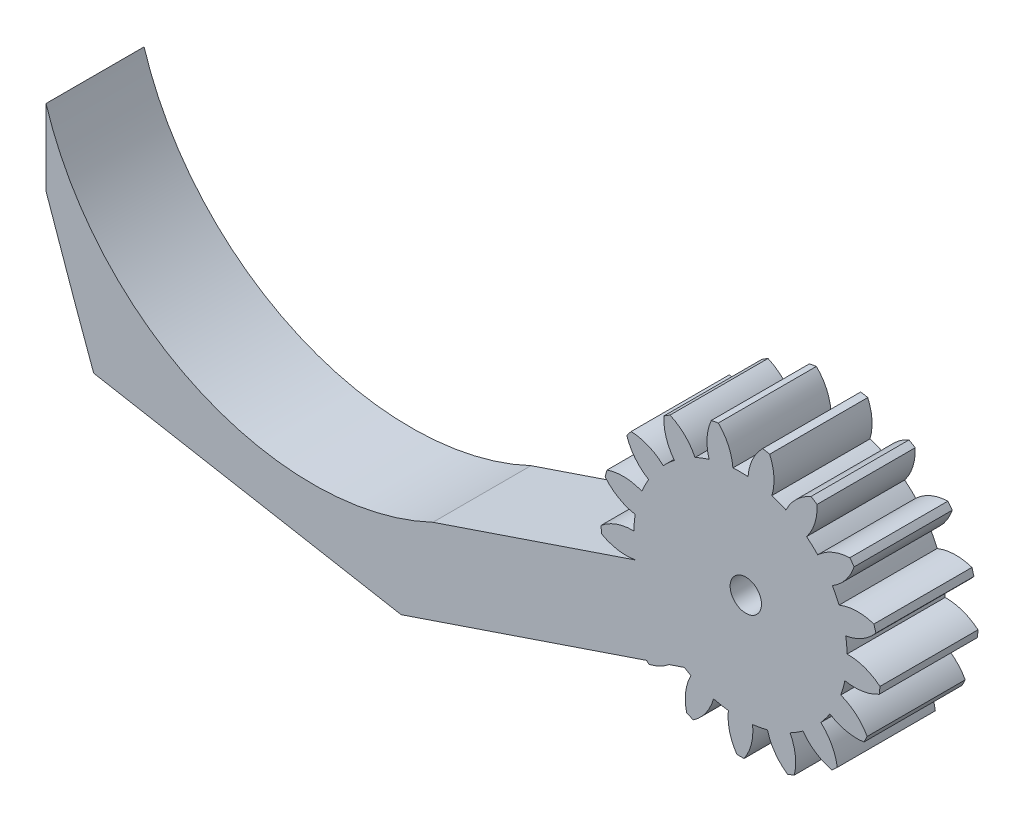
SolidWorks part; units mm, degrees
ref_plane "前视基准面" through (0, 0, 0) normal (0, 0, 1) x (1, 0, 0)
ref_plane "上视基准面" through (0, 0, 0) normal (0, 1, 0) x (1, 0, 0)
ref_plane "右视基准面" through (0, 0, 0) normal (1, 0, 0) x (0, 0, -1)
other "Configuration Table"
sketch "草图1" plane through (0, 0, 0) normal (0, 0, 1) x (1, 0, 0)
  circle A0 centre (-0.5445, -0.2729) radius 12.75 construction
  arc A1 (-14.346, 3.2738) -> (-11.274, 1.4939) centre (-10.4132, 6.5208) ccw
  arc A2 (-11.274, 1.4939) -> (-11.4159, -0.0382) centre (-0.5445, -0.2729) ccw
  arc A3 (-11.4159, -0.0382) -> (-14.7627, -1.2233) centre (-11.4935, -5.1376) ccw
  arc A4 (-14.7627, -1.2233) -> (-14.6953, -1.9514) centre (-0.5445, -0.2729) ccw
  arc A5 (-14.6953, -1.9514) -> (-11.1877, -2.5013) centre (-12.2009, 2.497) ccw
  arc A6 (-11.1877, -2.5013) -> (-10.7666, -3.9813) centre (-0.5445, -0.2729) ccw
  arc A7 (-10.7666, -3.9813) -> (-13.4593, -6.2953) centre (-8.9968, -8.7644) ccw
  arc A8 (-13.4593, -6.2953) -> (-13.1334, -6.9499) centre (-0.5445, -0.2729) ccw
  arc A9 (-13.1334, -6.9499) -> (-9.664, -6.1956) centre (-12.4144, -1.9008) ccw
  arc A10 (-9.664, -6.1956) -> (-8.7367, -7.4235) centre (-0.5445, -0.2729) ccw
  arc A11 (-8.7367, -7.4235) -> (-10.4117, -10.554) centre (-5.3586, -11.2443) ccw
  arc A12 (-10.4117, -10.554) -> (-9.8713, -11.0467) centre (-0.5445, -0.2729) ccw
  arc A13 (-9.8713, -11.0467) -> (-6.9087, -9.09) centre (-11.0248, -6.0788) ccw
  arc A14 (-6.9087, -9.09) -> (-5.6004, -9.9) centre (-0.5445, -0.2729) ccw
  arc A15 (-5.6004, -9.9) -> (-6.0314, -13.4242) centre (-1.0702, -12.2425) ccw
  arc A16 (-6.0314, -13.4242) -> (-5.3495, -13.6884) centre (-0.5445, -0.2729) ccw
  arc A17 (-5.3495, -13.6884) -> (-3.2938, -10.7936) centre (-8.2198, -9.4727) ccw
  arc A18 (-3.2938, -10.7936) -> (-1.7813, -11.0764) centre (-0.5445, -0.2729) ccw
  arc A19 (-1.7813, -11.0764) -> (-0.9101, -14.5183) centre (3.2892, -11.6241) ccw
  arc A20 (-0.9101, -14.5183) -> (-0.1788, -14.5183) centre (-0.5445, -0.2729) ccw
  arc A21 (-0.1788, -14.5183) -> (0.6924, -11.0764) centre (-4.3781, -11.6241) ccw
  arc A22 (0.6924, -11.0764) -> (2.2049, -10.7936) centre (-0.5445, -0.2729) ccw
  arc A23 (2.2049, -10.7936) -> (4.2606, -13.6884) centre (7.1308, -9.4727) ccw
  arc A24 (4.2606, -13.6884) -> (4.9425, -13.4242) centre (-0.5445, -0.2729) ccw
  arc A25 (4.9425, -13.4242) -> (4.5115, -9.9) centre (-0.0187, -12.2425) ccw
  arc A26 (4.5115, -9.9) -> (5.8197, -9.09) centre (-0.5445, -0.2729) ccw
  arc A27 (5.8197, -9.09) -> (8.7823, -11.0467) centre (9.9359, -6.0788) ccw
  arc A28 (8.7823, -11.0467) -> (9.3227, -10.554) centre (-0.5445, -0.2729) ccw
  arc A29 (9.3227, -10.554) -> (7.6478, -7.4235) centre (4.2697, -11.2443) ccw
  arc A30 (7.6478, -7.4235) -> (8.5751, -6.1956) centre (-0.5445, -0.2729) ccw
  arc A31 (8.5751, -6.1956) -> (12.0444, -6.9499) centre (11.3255, -1.9008) ccw
  arc A32 (12.0444, -6.9499) -> (12.3704, -6.2953) centre (-0.5445, -0.2729) ccw
  arc A33 (12.3704, -6.2953) -> (9.6777, -3.9813) centre (7.9079, -8.7644) ccw
  arc A34 (9.6777, -3.9813) -> (10.0988, -2.5013) centre (-0.5445, -0.2729) ccw
  arc A35 (10.0988, -2.5013) -> (13.6063, -1.9514) centre (11.112, 2.497) ccw
  arc A36 (13.6063, -1.9514) -> (13.6738, -1.2233) centre (-0.5445, -0.2729) ccw
  arc A37 (13.6738, -1.2233) -> (10.327, -0.0382) centre (10.4046, -5.1376) ccw
  arc A38 (10.327, -0.0382) -> (10.185, 1.4939) centre (-0.5445, -0.2729) ccw
  arc A39 (10.185, 1.4939) -> (13.2571, 3.2738) centre (9.3243, 6.5208) ccw
  arc A40 (13.2571, 3.2738) -> (13.057, 3.9771) centre (-0.5445, -0.2729) ccw
  arc A41 (13.057, 3.9771) -> (9.5081, 3.8732) centre (11.4225, -0.8539) ccw
  arc A42 (9.5081, 3.8732) -> (8.8222, 5.2506) centre (-0.5445, -0.2729) ccw
  arc A43 (8.8222, 5.2506) -> (11.0439, 8.02) centre (6.2037, 9.627) ccw
  arc A44 (11.0439, 8.02) -> (10.6032, 8.6035) centre (-0.5445, -0.2729) ccw
  arc A45 (10.6032, 8.6035) -> (7.3315, 7.2246) centre (10.8243, 3.5083) ccw
  arc A46 (7.3315, 7.2246) -> (6.1944, 8.2612) centre (-0.5445, -0.2729) ccw
  arc A47 (6.1944, 8.2612) -> (7.2656, 11.6462) centre (2.1717, 11.3962) ccw
  arc A48 (7.2656, 11.6462) -> (6.6439, 12.0311) centre (-0.5445, -0.2729) ccw
  arc A49 (6.6439, 12.0311) -> (4.0912, 9.5634) centre (8.6906, 7.3599) ccw
  arc A50 (4.0912, 9.5634) -> (2.6564, 10.1193) centre (-0.5445, -0.2729) ccw
  arc A51 (2.6564, 10.1193) -> (2.4325, 13.6626) centre (-2.2271, 11.5894) ccw
  arc A52 (2.4325, 13.6626) -> (1.7137, 13.797) centre (-0.5445, -0.2729) ccw
  arc A53 (1.7137, 13.797) -> (0.2249, 10.5738) centre (5.3097, 10.1805) ccw
  arc A54 (0.2249, 10.5738) -> (-1.3138, 10.5738) centre (-0.5445, -0.2729) ccw
  arc A55 (-1.3138, 10.5738) -> (-2.8026, 13.797) centre (-6.3986, 10.1805) ccw
  arc A56 (-2.8026, 13.797) -> (-3.5214, 13.6626) centre (-0.5445, -0.2729) ccw
  arc A57 (-3.5214, 13.6626) -> (-3.7454, 10.1193) centre (1.1382, 11.5894) ccw
  arc A58 (-3.7454, 10.1193) -> (-5.1802, 9.5634) centre (-0.5445, -0.2729) ccw
  arc A59 (-5.1802, 9.5634) -> (-7.7328, 12.0311) centre (-9.7795, 7.3599) ccw
  arc A60 (-7.7328, 12.0311) -> (-8.3545, 11.6462) centre (-0.5445, -0.2729) ccw
  arc A61 (-8.3545, 11.6462) -> (-7.2833, 8.2612) centre (-3.2606, 11.3962) ccw
  arc A62 (-7.2833, 8.2612) -> (-8.4204, 7.2246) centre (-0.5445, -0.2729) ccw
  arc A63 (-8.4204, 7.2246) -> (-11.6921, 8.6035) centre (-11.9132, 3.5083) ccw
  arc A64 (-11.6921, 8.6035) -> (-12.1328, 8.02) centre (-0.5445, -0.2729) ccw
  arc A65 (-12.1328, 8.02) -> (-9.9111, 5.2506) centre (-7.2926, 9.627) ccw
  arc A66 (-9.9111, 5.2506) -> (-10.597, 3.8732) centre (-0.5445, -0.2729) ccw
  arc A67 (-10.597, 3.8732) -> (-14.1459, 3.9771) centre (-12.5114, -0.8539) ccw
  arc A68 (-14.1459, 3.9771) -> (-14.346, 3.2738) centre (-0.5445, -0.2729) ccw
extrude "凸台-拉伸1" add sketch "草图1" along normal blind 10
sketch "草图2" plane through (0, 0, 10) normal (0, 0, 1) x (1, 0, 0)
  circle A0 centre (0, 0) radius 1.6
  dimension "D1" = 3.2
extrude "切除-拉伸1" cut sketch "草图2" against normal blind 10
sketch "草图3" plane through (0, 0, 10) normal (0, 0, 1) x (1, 0, 0)
  line L0 (-35.1456, -19.2998) -> (-6.2689, -9.5182)
  line L1 (-11.1877, -2.5013) -> (-31.9027, -9.5182)
  line L2 (-71.3541, 7.7364) -> (-71.3541, 0)
  line L3 (-71.3541, 0) -> (-68.4519, -8.2593)
  line L4 (-35.1456, -19.2998) -> (-66.4921, -13.6485)
  line L5 (-11.1877, -2.5013) -> (-6.2689, -9.5182)
  line L6 (-66.4921, -13.6485) -> (-68.4519, -8.2593)
  arc A0 (-31.9027, -9.5182) -> (-71.3541, 7.7364) centre (-44.1412, 16.228) cw
  arc A1 (-6.9087, -9.09) -> (-5.6004, -9.9) centre (-0.5445, -0.2729) ccw construction
extrude "凸台-拉伸2" add sketch "草图3" against normal blind 10
